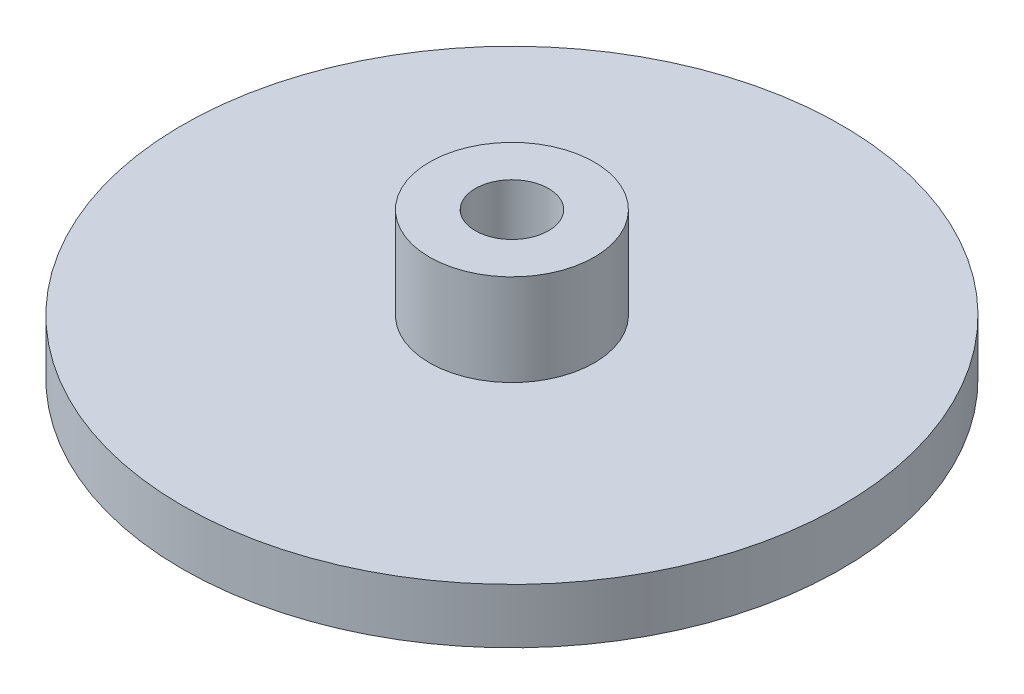
SolidWorks part; units mm, degrees
ref_plane "Front Plane" through (0, 0, 0) normal (0, 0, 1) x (1, 0, 0)
ref_plane "Top Plane" through (0, 0, 0) normal (0, 1, 0) x (1, 0, 0)
ref_plane "Right Plane" through (0, 0, 0) normal (1, 0, 0) x (0, 0, -1)
sketch "Sketch1" plane through (0, 0, 0) normal (0, 1, 0) x (1, 0, 0)
  circle A0 centre (0, 0) radius 36
  dimension "D1" = 72
extrude "Boss-Extrude1" add sketch "Sketch1" along normal blind 6
sketch "Sketch2" plane through (0, 6, 0) normal (0, 1, 0) x (1, 0, 0)
  circle A0 centre (0, 0) radius 9
  dimension "D1" = 18
extrude "Boss-Extrude2" add sketch "Sketch2" along normal blind 10
sketch "Sketch3" plane through (0, 16, 0) normal (0, 1, 0) x (1, 0, 0)
  circle A0 centre (0, 0) radius 4
  dimension "D1" = 8
extrude "Cut-Extrude1" cut sketch "Sketch3" against normal through all
